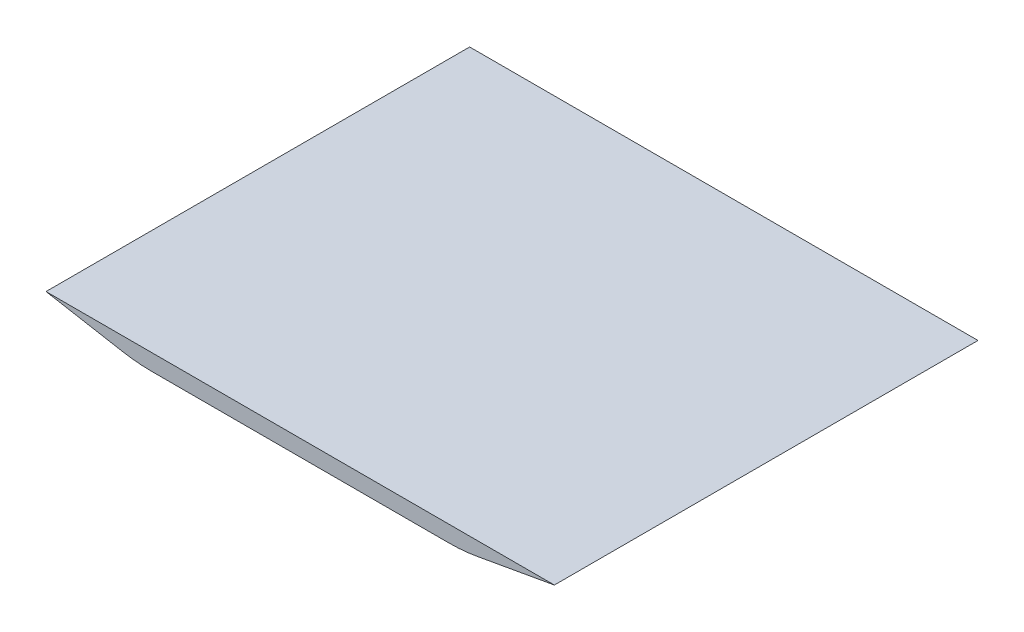
SolidWorks part; units mm, degrees
ref_plane "Front Plane" through (0, 0, 0) normal (0, 0, 1) x (1, 0, 0)
ref_plane "Top Plane" through (0, 0, 0) normal (0, 1, 0) x (1, 0, 0)
ref_plane "Right Plane" through (0, 0, 0) normal (1, 0, 0) x (0, 0, -1)
sketch "Sketch1" plane through (0, 0, 0) normal (0, 0, 1) x (1, 0, 0)
  line L0 (0, 0) -> (156, 0)
  line L1 (156, 0) -> (128, -5)
  line L2 (128, -5) -> (28, -5)
  line L3 (28, -5) -> (0, 0)
  dimension "D1" = 100
  dimension "D2" = 5
  dimension "D3" = 28
  dimension "D4" = 28
extrude "Boss-Extrude1" add sketch "Sketch1" along normal blind 130
fillet "Fillet1" radius 50 2 edges at (28, -5, 65) (128, -5, 65)
